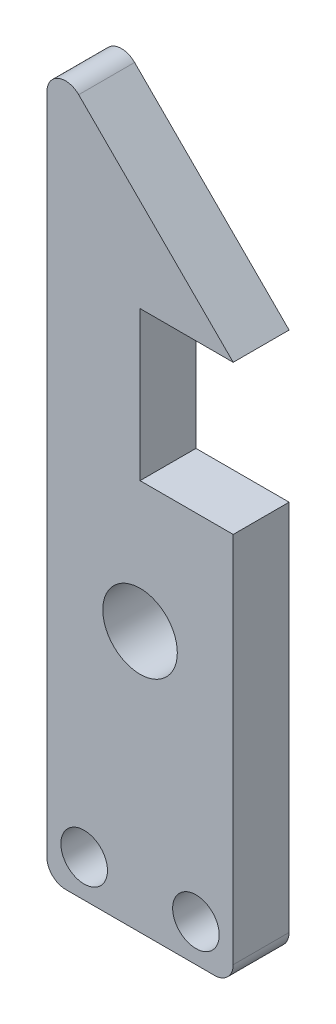
SolidWorks part; units mm, degrees
ref_plane "前视基准面" through (0, 0, 0) normal (0, 0, 1) x (1, 0, 0)
ref_plane "上视基准面" through (0, 0, 0) normal (0, 1, 0) x (1, 0, 0)
ref_plane "右视基准面" through (0, 0, 0) normal (1, 0, 0) x (0, 0, -1)
sketch "草图1" plane through (0, 0, 0) normal (0, 0, 1) x (1, 0, 0)
  line L0 (10, 0) -> (10, 21)
  line L1 (0, 0) -> (10, 0)
  line L2 (10, 21) -> (5, 21)
  line L3 (5, 21) -> (5, 29)
  line L4 (5, 29) -> (10, 29)
  line L5 (0, 0) -> (0, 39)
  line L6 (10, 29) -> (0, 39)
  circle A0 centre (5, 14) radius 2
  circle A1 centre (2, 2) radius 1.25
  circle A2 centre (8, 2) radius 1.25
  point P9 (5, 0)
  dimension "D1" = 4
  dimension "D4" = 2.5
  dimension "D5" = 2.5
  dimension "D2" = 10
  dimension "D3" = 14
  dimension "D6" = 2
  dimension "D7" = 2
  dimension "D8" = 2
  dimension "D9" = 21
  dimension "D10" = 8
  dimension "D11" = 5
  dimension "D12" = 45
  dimension "D13" = 5
extrude "凸台-拉伸1" add sketch "草图1" along normal blind 3
fillet "圆角1" radius 1 3 edges at (0, 39, 1.5) (10, 0, 1.5) (0, 0, 1.5)
